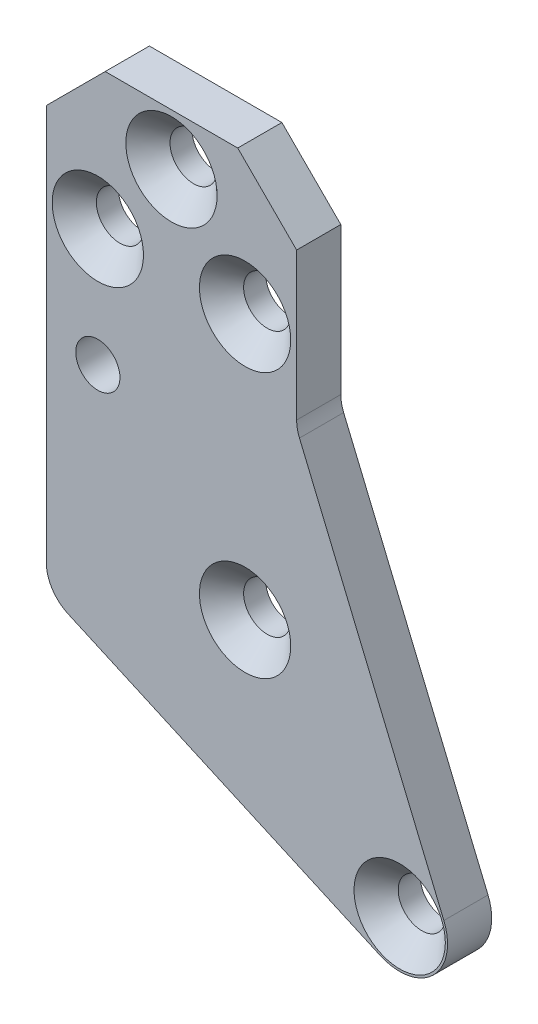
SolidWorks part; units mm, degrees
ref_plane "前视基准面" through (0, 0, 0) normal (0, 0, 1) x (1, 0, 0)
ref_plane "上视基准面" through (0, 0, 0) normal (0, 1, 0) x (1, 0, 0)
ref_plane "右视基准面" through (0, 0, 0) normal (1, 0, 0) x (0, 0, -1)
sketch "草图1" plane through (0, 0, 0) normal (0, 0, 1) x (1, 0, 0)
  line L0 (-3.5, 17.5) -> (-3.5, -15)
  line L1 (0, 0) -> (7.6906, 0) construction
  line L2 (7.6906, 0) -> (20.5, -22.1865) construction
  line L3 (-3.5, 17.5) -> (13.5, 17.5)
  line L4 (13.5, 17.5) -> (13.5, 3)
  line L5 (-3.5, -15) -> (19.1717, -25.1527)
  line L6 (13.5, 3) -> (23.4988, -20.9337)
  circle A0 centre (0, 0) radius 1.5
  circle A1 centre (10, -10) radius 1.6
  circle A2 centre (20.5, -22.1865) radius 1.6
  circle A3 centre (10, -4) radius 1.6 construction
  circle A4 centre (10, -10) radius 2.5 construction
  arc A5 (19.1717, -25.1527) -> (23.4988, -20.9337) centre (20.5, -22.1865) ccw
  circle A6 centre (0, 8) radius 1.6
  circle A7 centre (10, 8) radius 1.6
  circle A8 centre (5, 14) radius 1.6
  dimension "D1" = 3
  dimension "D4" = 3.2
  dimension "D6" = 3.2
  dimension "D9" = 5
  dimension "D11" = 6.5
  dimension "D2" = 10
  dimension "D3" = 10
  dimension "D5" = 3.5
  dimension "D7" = 30
  dimension "D8" = 4
  dimension "D10" = 21
  dimension "D12" = 3.5
  dimension "D13" = 10
  dimension "D14" = 5
  dimension "D15" = 6
  dimension "D16" = 3.5
  dimension "D17" = 5
  dimension "D18" = 3
  dimension "D19" = 15
extrude "凸台-拉伸1" add sketch "草图1" along normal mid plane 3
chamfer "倒角1" distance 1.5 angle 45 5 edges at (22.1, -22.1865, 1.5) (11.6, -10, 1.5) (11.6, 8, 1.5) (6.6, 14, 1.5) (1.6, 8, 1.5)
fillet "圆角1" radius 2.5 2 edges at (13.5, 3, 0) (-3.5, -15, 0)
chamfer "倒角2" distance 4 angle 45 2 edges at (13.5, 17.5, 0) (-3.5, 17.5, 0)
equation "\"D14@草图1\"=\"D13@草图1\"/2"
